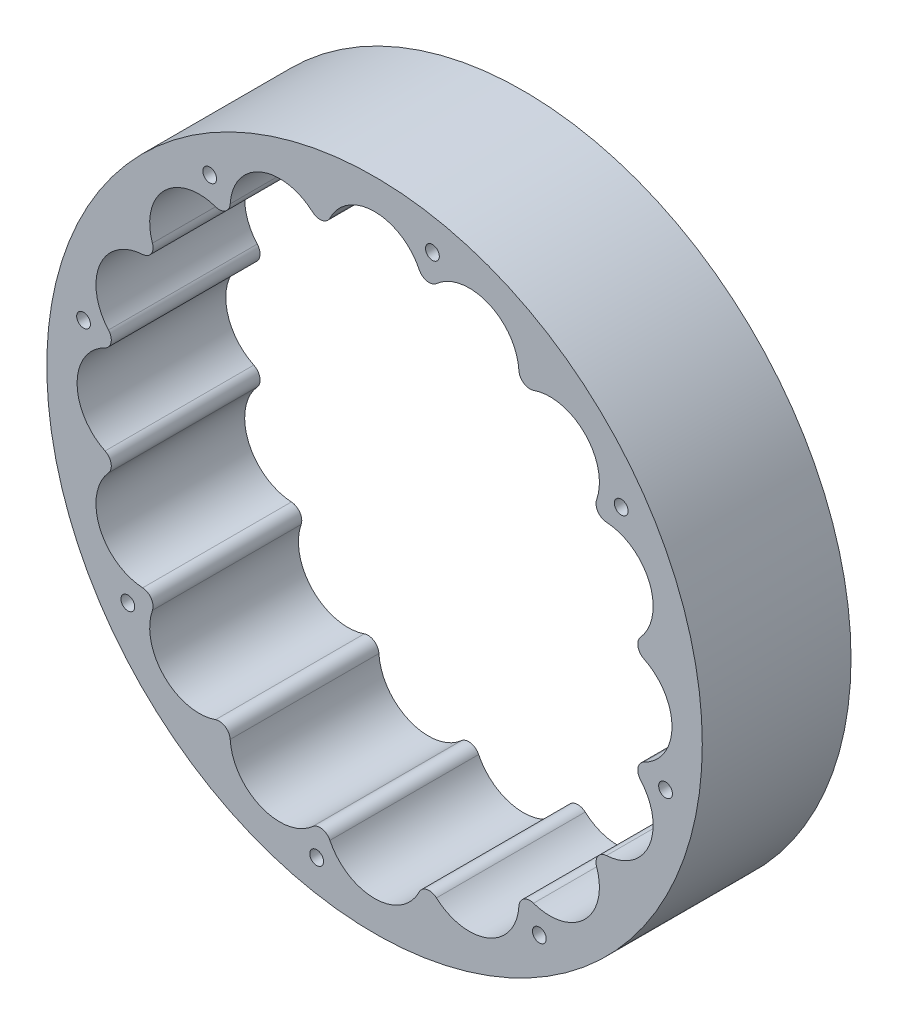
SolidWorks part; units mm, degrees
ref_plane "Front Plane" through (0, 0, 0) normal (0, 0, 1) x (1, 0, 0)
ref_plane "Top Plane" through (0, 0, 0) normal (0, 1, 0) x (1, 0, 0)
ref_plane "Right Plane" through (0, 0, 0) normal (1, 0, 0) x (0, 0, -1)
sketch "Sketch1" plane through (0, 0, 0) normal (0, 0, 1) x (1, 0, 0)
  circle A0 centre (0, 0) radius 59.5
  dimension "D1" = 119
extrude "Boss-Extrude1" add sketch "Sketch1" along normal blind 10
sketch "Sketch2" plane through (0, 0, 10) normal (0, 0, 1) x (1, 0, 0)
  line L0 (0, 0) -> (75.392, 0) construction
  circle A0 centre (0, 0) radius 45 construction
  arc A1 (45.2311, -8.997) -> (45.2311, 8.997) centre (45, 0) ccw
  arc A2 (38.3451, -25.6214) -> (45.2311, -8.997) centre (41.5746, -17.2208) ccw
  arc A3 (25.6214, -38.3451) -> (38.3451, -25.6214) centre (31.8198, -31.8198) ccw
  arc A4 (8.997, -45.2311) -> (25.6214, -38.3451) centre (17.2208, -41.5746) ccw
  arc A5 (-8.997, -45.2311) -> (8.997, -45.2311) centre (0, -45) ccw
  arc A6 (-25.6214, -38.3451) -> (-8.997, -45.2311) centre (-17.2208, -41.5746) ccw
  arc A7 (-38.3451, -25.6214) -> (-25.6214, -38.3451) centre (-31.8198, -31.8198) ccw
  arc A8 (-45.2311, -8.997) -> (-38.3451, -25.6214) centre (-41.5746, -17.2208) ccw
  arc A9 (-45.2311, 8.997) -> (-45.2311, -8.997) centre (-45, 0) ccw
  arc A10 (-38.3451, 25.6214) -> (-45.2311, 8.997) centre (-41.5746, 17.2208) ccw
  arc A11 (-25.6214, 38.3451) -> (-38.3451, 25.6214) centre (-31.8198, 31.8198) ccw
  arc A12 (-8.997, 45.2311) -> (-25.6214, 38.3451) centre (-17.2208, 41.5746) ccw
  arc A13 (8.997, 45.2311) -> (-8.997, 45.2311) centre (0, 45) ccw
  arc A14 (25.6214, 38.3451) -> (8.997, 45.2311) centre (17.2208, 41.5746) ccw
  arc A15 (38.3451, 25.6214) -> (25.6214, 38.3451) centre (31.8198, 31.8198) ccw
  arc A16 (45.2311, 8.997) -> (38.3451, 25.6214) centre (41.5746, 17.2208) ccw
  circle A17 centre (0, 0) radius 59.5
  point P38 (0, 0)
  dimension "D1" = 90
  dimension "D2" = 18
  dimension "D3" = 16
extrude "Boss-Extrude3" add sketch "Sketch2" along normal blind 27
sketch "Sketch3" plane through (0, 0, 10) normal (0, 0, 1) x (1, 0, 0)
  line L0 (0, 0) -> (77.0612, 0) construction
  circle A0 centre (0, 0) radius 45 construction
  circle A1 centre (45, 0) radius 2.025
  circle A2 centre (41.5746, -17.2208) radius 2.025
  circle A3 centre (31.8198, -31.8198) radius 2.025
  circle A4 centre (17.2208, -41.5746) radius 2.025
  circle A5 centre (0, -45) radius 2.025
  circle A6 centre (-17.2208, -41.5746) radius 2.025
  circle A7 centre (-31.8198, -31.8198) radius 2.025
  circle A8 centre (-41.5746, -17.2208) radius 2.025
  circle A9 centre (-45, 0) radius 2.025
  circle A10 centre (-41.5746, 17.2208) radius 2.025
  circle A11 centre (-31.8198, 31.8198) radius 2.025
  circle A12 centre (-17.2208, 41.5746) radius 2.025
  circle A13 centre (0, 45) radius 2.025
  circle A14 centre (17.2208, 41.5746) radius 2.025
  circle A15 centre (31.8198, 31.8198) radius 2.025
  circle A16 centre (41.5746, 17.2208) radius 2.025
  point P39 (0, 0)
  dimension "D1" = 90
  dimension "D2" = 4.05
  dimension "D3" = 16
extrude "Cut-Extrude1" cut sketch "Sketch3" against normal blind 4
sketch "Sketch4" plane through (0, 0, 10) normal (0, 0, 1) x (1, 0, 0)
  circle A0 centre (0, 0) radius 23.525
  dimension "D1" = 47.05
extrude "Cut-Extrude2" cut sketch "Sketch4" against normal blind 7
sketch "Sketch5" plane through (0, 0, 3) normal (0, 0, 1) x (1, 0, 0)
  circle A0 centre (0, 0) radius 18
  dimension "D1" = 36
extrude "Cut-Extrude3" cut sketch "Sketch5" against normal through all
sketch "Sketch6" plane through (0, 0, 37) normal (0, 0, 1) x (1, 0, 0)
  line L0 (0, 0) -> (73.8619, 0) construction
  line L1 (0, 0) -> (57.2955, 38.2836) construction
  circle A0 centre (44.783, 29.923) radius 1.25
  circle A1 centre (0, 0) radius 53.86 construction
  circle A2 centre (52.8251, -10.5076) radius 1.25
  circle A3 centre (29.923, -44.783) radius 1.25
  circle A4 centre (-10.5076, -52.8251) radius 1.25
  circle A5 centre (-44.783, -29.923) radius 1.25
  circle A6 centre (-52.8251, 10.5076) radius 1.25
  circle A7 centre (-29.923, 44.783) radius 1.25
  circle A8 centre (10.5076, 52.8251) radius 1.25
  point P25 (0, 0)
  dimension "D1" = 107.72
  dimension "D2" = 2.5
  dimension "D3" = 8
extrude "Cut-Extrude4" cut sketch "Sketch6" against normal blind 22
fillet "Fillet1" radius 2 16 edges at (-25.6214, -38.3451, 23.5) (-38.3451, -25.6214, 23.5) (-45.2311, -8.997, 23.5) (-45.2311, 8.997, 23.5) (-8.997, -45.2311, 23.5) (8.997, -45.2311, 23.5) (25.6214, -38.3451, 23.5) (38.3451, -25.6214, 23.5) (45.2311, -8.997, 23.5) (45.2311, 8.997, 23.5) (38.3451, 25.6214, 23.5) (25.6214, 38.3451, 23.5) (8.997, 45.2311, 23.5) (-8.997, 45.2311, 23.5) (-25.6214, 38.3451, 23.5) (-38.3451, 25.6214, 23.5)
sketch "Sketch7" plane through (0, 0, 10) normal (0, 0, 1) x (1, 0, 0)
  line L1 (64.8205, -63.9859) -> (-73.8619, -63.9859)
  line L2 (64.8205, -63.9859) -> (64.8205, 62.1776)
  line L3 (64.8205, 62.1776) -> (-73.8619, 62.1776)
  line L4 (-73.8619, -63.9859) -> (-73.8619, 62.1776)
  point P4 (64.8205, -63.9859)
extrude "Cut-Extrude5" cut sketch "Sketch7" against normal blind 0.01
delete or keep bodies "Body-Delete/Keep 2" type delete bodies bodies 110
sketch "Sketch8" plane through (0, 0, 10) normal (0, 0, -1) x (-1, 0, 0)
  line L0 (0, 0) -> (60.724, 40.5745) construction
  circle A0 centre (0, 0) radius 54 construction
  circle A1 centre (44.8994, 30.0008) radius 1.5
  circle A2 centre (52.9624, -10.5349) radius 1.5
  circle A3 centre (30.0008, -44.8994) radius 1.5
  circle A4 centre (-10.5349, -52.9624) radius 1.5
  circle A5 centre (-44.8994, -30.0008) radius 1.5
  circle A6 centre (-52.9624, 10.5349) radius 1.5
  circle A7 centre (-30.0008, 44.8994) radius 1.5
  circle A8 centre (10.5349, 52.9624) radius 1.5
  point P23 (0, 0)
  dimension "D1" = 108
  dimension "D2" = 3
  dimension "D3" = 8
extrude "Cut-Extrude6" cut sketch "Sketch8" against normal blind 22
sketch "Sketch9" plane through (0, 0, 10) normal (0, 0, -1) x (-1, 0, 0)
  circle A0 centre (0, 0) radius 57.25
  circle A1 centre (0, 0) radius 59.5 construction
  circle A2 centre (0, 0) radius 58.3
  circle A3 centre (0, 0) radius 56.2
  dimension "D1" = 2.25
  dimension "D2" = 1.05
  dimension "D3" = 1.05
extrude "Cut-Extrude7" cut sketch "Sketch9" against normal blind 2.1 contours A3 | A2
